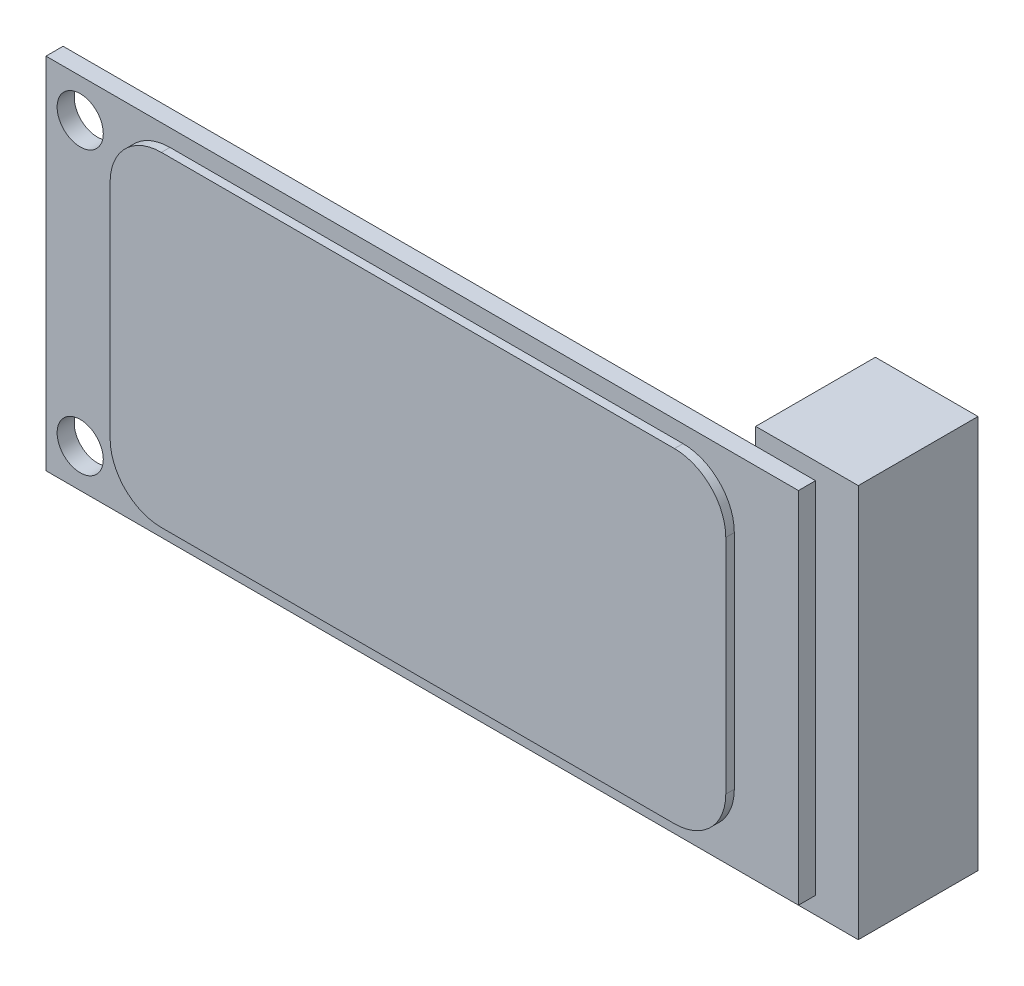
SolidWorks part; units mm, degrees
ref_plane "Front Plane" through (0, 0, 0) normal (0, 0, 1) x (1, 0, 0)
ref_plane "Top Plane" through (0, 0, 0) normal (0, 1, 0) x (1, 0, 0)
ref_plane "Right Plane" through (0, 0, 0) normal (1, 0, 0) x (0, 0, -1)
sketch "Sketch1" plane through (0, 0, 0) normal (0, 0, 1) x (1, 0, 0)
  line L1 (20, -8.25) -> (-20, -8.25)
  line L2 (20, -8.25) -> (20, 8.25)
  line L3 (20, 8.25) -> (-20, 8.25)
  line L4 (-20, -8.25) -> (-20, 8.25)
  line L5 (20, -8.25) -> (-20, 8.25) construction
  line L6 (20, 8.25) -> (-20, -8.25) construction
  line L7 (22, -10.5) -> (-22, -10.5)
  line L8 (22, -10.5) -> (22, 10.5)
  line L9 (22, 10.5) -> (-22, 10.5)
  line L10 (-22, -10.5) -> (-22, 10.5)
  line L11 (22, -10.5) -> (-22, 10.5) construction
  line L12 (22, 10.5) -> (-22, -10.5) construction
  circle A0 centre (-20, 8.25) radius 1.35
  circle A1 centre (-20, -8.25) radius 1.35
  point P0 (0, 0)
  point P6 (0, 0)
  dimension "D1" = 2.7
  dimension "D3" = 2
  dimension "D4" = 2.25
  dimension "D2" = 16.5
  dimension "D5" = 44
extrude "Boss-Extrude1" add sketch "Sketch1" along normal blind 1 contours L10 L7 L8 L9 A1 L4 A0 L3 L2 L1 | A1 L1 L2 L3 A0 L4
sketch "Sketch2" plane through (0, 0, 1) normal (0, 0, 1) x (1, 0, 0)
  line L0 (-22, -10.5) -> (-22, 10.5) construction
  line L1 (-17.75, -9.5) -> (18.25, -9.5)
  line L2 (-17.75, -9.5) -> (-17.75, 9.5)
  line L3 (-17.75, 9.5) -> (18.25, 9.5)
  line L4 (18.25, -9.5) -> (18.25, 9.5)
  line L5 (-17.75, -9.5) -> (18.25, 9.5) construction
  line L6 (-17.75, 9.5) -> (18.25, -9.5) construction
  line L7 (22, 10.5) -> (-22, 10.5) construction
  line L8 (22, -10.5) -> (-22, -10.5) construction
  point P0 (0.25, 0)
  dimension "D1" = 4.25
  dimension "D2" = 1
  dimension "D3" = 1
  dimension "D4" = 36
extrude "Boss-Extrude2" add sketch "Sketch2" along normal blind 0.5 contours L2 L1 L4 L3
fillet "Fillet1" radius 3 4 edges at (18.25, 9.5, 1.25) (18.25, -9.5, 1.25) (-17.75, -9.5, 1.25) (-17.75, 9.5, 1.25)
sketch "Sketch3" plane through (0, 0, 0) normal (0, 0, -1) x (-1, 0, 0)
  line L0 (-22, -10.5) -> (-22, 10.5) construction
  line L1 (-24.5, 11.5) -> (-18.5, 11.5)
  line L2 (-24.5, 11.5) -> (-24.5, -11.5)
  line L3 (-24.5, -11.5) -> (-18.5, -11.5)
  line L4 (-18.5, 11.5) -> (-18.5, -11.5)
  line L5 (-22, 10.5) -> (22, 10.5) construction
  dimension "D1" = 3.5
  dimension "D2" = 6
  dimension "D3" = 23
  dimension "D4" = 1
extrude "Boss-Extrude3" add sketch "Sketch3" along normal blind 7
